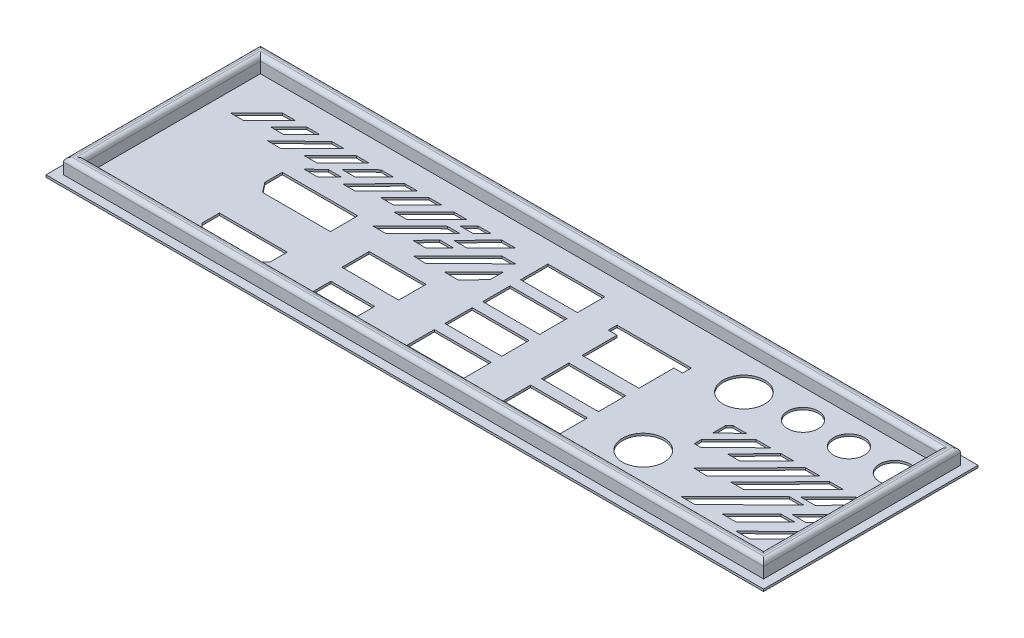
SolidWorks part; units mm, degrees
ref_plane "Front Plane" through (0, 0, 0) normal (0, 0, 1) x (1, 0, 0)
ref_plane "Top Plane" through (0, 0, 0) normal (0, 1, 0) x (1, 0, 0)
ref_plane "Right Plane" through (0, 0, 0) normal (1, 0, 0) x (0, 0, -1)
sketch "Sketch1" plane through (0, 0, 0) normal (0, 1, 0) x (1, 0, 0)
  line L1 (-77.5, -20) -> (77.5, -20)
  line L2 (-77.5, -20) -> (-77.5, 20)
  line L3 (-77.5, 20) -> (77.5, 20)
  line L4 (77.5, -20) -> (77.5, 20)
  line L5 (-77.5, -20) -> (77.5, 20) construction
  line L6 (-77.5, 20) -> (77.5, -20) construction
  point P0 (0, 0)
  dimension "D1" = 40
  dimension "D2" = 155
extrude "Boss-Extrude1" add sketch "Sketch1" along normal blind 0.5
sketch "Sketch2" plane through (0, 0, 0) normal (0, -1, 0) x (1, 0, 0)
  line L0 (-80, 22.5) -> (80, 22.5)
  line L1 (-77.5, -20) -> (77.5, -20)
  line L2 (-77.5, -20) -> (-77.5, 20)
  line L3 (-77.5, 20) -> (77.5, 20)
  line L4 (77.5, -20) -> (77.5, 20)
  line L5 (-77.5, -20) -> (77.5, 20) construction
  line L6 (-77.5, 20) -> (77.5, -20) construction
  line L7 (80, -22.5) -> (80, 22.5)
  line L8 (-80, -22.5) -> (80, -22.5)
  line L9 (-80, -22.5) -> (-80, 22.5)
  point P0 (0, 0)
  dimension "D1" = 2.5
extrude "Boss-Extrude2" add sketch "Sketch2" against normal blind 4
fillet "Fillet1" radius 1 8 edges at (0, 4, -22.5) (80, 4, 0) (0, 4, 22.5) (-80, 4, 0) (0, 4, -20) (-77.5, 4, 0) (0, 4, 20) (77.5, 4, 0)
sketch "Sketch3" plane through (0, 0, 0) normal (0, -1, 0) x (1, 0, 0)
  line L14 (-82, -24.5) -> (82, -24.5)
  line L15 (82, -24.5) -> (82, 24.5)
  line L16 (82, 24.5) -> (-82, 24.5)
  line L17 (-82, 24.5) -> (-82, -24.5)
  line L18 (-82, -24.5) -> (82, -24.5)
  line L19 (82, -24.5) -> (82, 24.5)
  line L20 (82, 24.5) -> (-82, 24.5)
  line L21 (-82, 24.5) -> (-82, -24.5)
  dimension "D1" = 2
extrude "Boss-Extrude3" add sketch "Sketch3" against normal blind 0.5
sketch "Sketch5" plane through (0, 0.5, 0) normal (0, 1, 0) x (1, 0, 0)
  line L0 (77.5, -20) -> (77.5, 20) construction
  line L1 (77.5, 20) -> (-77.5, 20) construction
  line L2 (-77.5, -20) -> (77.5, -20) construction
  line L3 (15, -17) -> (28, -17)
  line L4 (15, -17) -> (15, -10.75)
  line L5 (15, -10.75) -> (28, -10.75)
  line L6 (28, -17) -> (28, -10.75)
  line L7 (15, -8.25) -> (28, -8.25)
  line L8 (15, -8.25) -> (15, -2)
  line L9 (15, -2) -> (28, -2)
  line L10 (28, -8.25) -> (28, -2)
  line L11 (13, 11) -> (13, 9)
  line L12 (13, 9) -> (15, 9)
  line L13 (15, 9) -> (15, 1)
  line L14 (15, 1) -> (28, 1)
  line L15 (28, 1) -> (28, 9)
  line L16 (28, 9) -> (30, 9)
  line L17 (30, 9) -> (30, 11)
  line L18 (30, 11) -> (13, 11)
  line L19 (-77.5, -20) -> (77.5, -20) construction
  line L20 (-7, -17) -> (6, -17)
  line L21 (-7, -17) -> (-7, -10.75)
  line L22 (-7, -10.75) -> (6, -10.75)
  line L23 (6, -17) -> (6, -10.75)
  line L24 (-7, -8.35) -> (6, -8.35)
  line L25 (-7, -8.35) -> (-7, -2.1)
  line L26 (-7, -2.1) -> (6, -2.1)
  line L27 (6, -8.35) -> (6, -2.1)
  line L28 (6, 0.3) -> (-7, 0.3)
  line L29 (6, 0.3) -> (6, 6.55)
  line L30 (6, 6.55) -> (-7, 6.55)
  line L31 (-7, 0.3) -> (-7, 6.55)
  line L32 (-7, 8.95) -> (6, 8.95)
  line L33 (-7, 8.95) -> (-7, 15.2)
  line L34 (-7, 15.2) -> (6, 15.2)
  line L35 (6, 8.95) -> (6, 15.2)
  line L36 (-29.8898, -9) -> (-16.8898, -9)
  line L37 (-29.8898, -9) -> (-29.8898, -2.75)
  line L38 (-29.8898, -2.75) -> (-16.8898, -2.75)
  line L39 (-16.8898, -9) -> (-16.8898, -2.75)
  line L40 (-28.3898, -17) -> (-18.3898, -17)
  line L41 (-28.3898, -17) -> (-28.3898, -13)
  line L42 (-28.3898, -13) -> (-18.3898, -13)
  line L43 (-18.3898, -17) -> (-18.3898, -13)
  line L44 (-55.5, 3) -> (-55.5, -1)
  line L45 (-55.5, -1) -> (-53.75, -3.25)
  line L46 (-53.75, -3.25) -> (-38.25, -3.25)
  line L47 (-38.25, -3.25) -> (-38.25, 3)
  line L48 (-38.25, 3) -> (-55.5, 3)
  line L50 (-39.125, -12.25) -> (-39.125, -16.25)
  line L52 (-41.375, -18.25) -> (-52.375, -18.25)
  line L54 (-54.625, -16.25) -> (-54.625, -12.25)
  line L55 (-41.375, -18.25) -> (-39.125, -16.25)
  line L56 (-52.375, -18.25) -> (-54.625, -16.25)
  line L57 (-77.5, 20) -> (-77.5, -20) construction
  line L58 (-54.625, -12.25) -> (-39.125, -12.25)
  circle A0 centre (74, 13.5) radius 3.5
  circle A1 centre (63.5, 13.5) radius 3.5
  circle A2 centre (53, 13.5) radius 3.5
  circle A3 centre (40.75, 12.25) radius 4.75
  circle A4 centre (40.75, -10.75) radius 4.75
  dimension "D1" = 7
  dimension "D2" = 3.5
  dimension "D4" = 7
  dimension "D5" = 7
  dimension "D6" = 6.5
  dimension "D7" = 6.5
  dimension "D8" = 10.5
  dimension "D9" = 10.5
  dimension "D10" = 9.5
  dimension "D11" = 9.5
  dimension "D12" = 7.75
  dimension "D13" = 23
  dimension "D14" = 36.75
  dimension "D15" = 36.75
  dimension "D3" = 6.5
  dimension "D16" = 6.25
  dimension "D17" = 13
  dimension "D18" = 6.25
  dimension "D19" = 13
  dimension "D20" = 3
  dimension "D21" = 2.5
  dimension "D22" = 3
  dimension "D23" = 13
  dimension "D24" = 8
  dimension "D25" = 2
  dimension "D26" = 2
  dimension "D27" = 2
  dimension "D28" = 2
  dimension "D29" = 49.5
  dimension "D30" = 6.25
  dimension "D31" = 6.25
  dimension "D32" = 6.25
  dimension "D33" = 6.25
  dimension "D34" = 13
  dimension "D35" = 13
  dimension "D36" = 13
  dimension "D37" = 13
  dimension "D38" = 2.4
  dimension "D39" = 2.4
  dimension "D40" = 2.4
  dimension "D41" = 3
  dimension "D42" = 71.5
  dimension "D43" = 13
  dimension "D44" = 6.25
  dimension "D45" = 4
  dimension "D46" = 10
  dimension "D47" = 4
  dimension "D48" = 3
  dimension "D49" = 17.25
  dimension "D50" = 1.5
  dimension "D51" = 6.25
  dimension "D52" = 15.5
  dimension "D53" = 15.5
  dimension "D54" = 9
  dimension "D55" = 11
  dimension "D56" = 4
  dimension "D57" = 4
  dimension "D58" = 2.25
  dimension "D59" = 0.875
  dimension "D60" = 22
  dimension "D61" = 17
  dimension "D62" = 4
  dimension "D63" = 6
extrude "Cut-Extrude1" cut sketch "Sketch5" against normal through all
sketch "Sketch7" plane through (0, 0.5, 0) normal (0, 1, 0) x (1, 0, 0)
  line L0 (-67.2505, 14.7466) -> (-64.2392, 14.7466)
  line L1 (-64.2392, 14.7466) -> (-70.1769, 8.8089)
  line L2 (-70.1769, 8.8089) -> (-73.2004, 8.8089)
  line L3 (-73.2004, 8.8089) -> (-67.2505, 14.7466)
  line L4 (-61.6406, 14.7466) -> (-58.7264, 14.7466)
  line L5 (-58.7264, 14.7466) -> (-62.859, 10.6224)
  line L6 (-62.859, 10.6224) -> (-65.7448, 10.6224)
  line L7 (-65.7448, 10.6224) -> (-61.6406, 14.7466)
  line L8 (-55.8851, 14.7466) -> (-53.1651, 14.7466)
  line L9 (-53.1651, 14.7466) -> (-60.336, 7.5408)
  line L10 (-60.336, 7.5408) -> (-63.4377, 7.5408)
  line L11 (-63.4377, 7.5408) -> (-55.8851, 14.7466)
  line L12 (-50.3238, 14.7466) -> (-47.4096, 14.7466)
  line L13 (-47.4096, 14.7466) -> (-53.3185, 8.8089)
  line L14 (-53.3185, 8.8089) -> (-56.3465, 8.8089)
  line L15 (-56.3465, 8.8089) -> (-50.3238, 14.7466)
  line L16 (-44.7382, 14.7466) -> (-41.8968, 14.7466)
  line L17 (-41.8968, 14.7466) -> (-46.3352, 10.3708)
  line L18 (-46.3352, 10.3708) -> (-49.2795, 10.3708)
  line L19 (-49.2795, 10.3708) -> (-44.7382, 14.7466)
  line L20 (-50.7366, 8.8089) -> (-47.8074, 8.8089)
  line L21 (-47.8074, 8.8089) -> (-50.6074, 6.1109)
  line L22 (-50.6074, 6.1109) -> (-53.6866, 6.1109)
  line L23 (-53.6866, 6.1109) -> (-50.7366, 8.8089)
  line L24 (-39.2255, 14.7466) -> (-36.2627, 14.7466)
  line L25 (-36.2627, 14.7466) -> (-43.4147, 7.5946)
  line L26 (-43.4147, 7.5946) -> (-46.3352, 7.5946)
  line L27 (-46.3352, 7.5946) -> (-39.2255, 14.7466)
  line L28 (-33.567, 14.7466) -> (-30.7742, 14.7466)
  line L29 (-30.7742, 14.7466) -> (-36.2627, 9.2256)
  line L30 (-36.2627, 9.2256) -> (-39.2255, 9.2256)
  line L31 (-39.2255, 9.2256) -> (-33.737, 14.7466)
  line L32 (-33.737, 14.7466) -> (-33.567, 14.7466)
  line L33 (-28.0398, 14.7466) -> (-25.0141, 14.7466)
  line L34 (-25.0141, 14.7466) -> (-31.833, 7.8872)
  line L35 (-31.833, 7.8872) -> (-34.9164, 7.8872)
  line L36 (-34.9164, 7.8872) -> (-28.0398, 14.7466)
  line L37 (-22.5741, 14.7466) -> (-19.5809, 14.7466)
  line L38 (-19.5809, 14.7466) -> (-21.648, 12.6846)
  line L39 (-21.648, 12.6846) -> (-24.461, 12.6846)
  line L40 (-24.461, 12.6846) -> (-22.5741, 14.7466)
  line L41 (-25.9576, 11.1706) -> (-23.0545, 11.1706)
  line L42 (-23.0545, 11.1706) -> (-31.5441, 2.7023)
  line L43 (-31.5441, 2.7023) -> (-34.563, 2.7023)
  line L44 (-34.563, 2.7023) -> (-25.9576, 11.1706)
  line L45 (-27.0963, 4.4196) -> (-24.1194, 4.4196)
  line L46 (-24.1194, 4.4196) -> (-20.893, 7.5946)
  line L47 (-20.893, 7.5946) -> (-24.1194, 7.5946)
  line L48 (-24.1194, 7.5946) -> (-27.0963, 4.4196)
  line L49 (-22.3788, 9.1044) -> (-19.4508, 9.1044)
  line L50 (-19.4508, 9.1044) -> (-13.8097, 14.6556)
  line L51 (-13.8097, 14.6556) -> (-17.0595, 14.6556)
  line L52 (-17.0595, 14.6556) -> (-22.3788, 9.1044)
  line L53 (-23.8985, 1.4213) -> (-21.0775, 1.3284)
  line L54 (-21.0775, 1.3284) -> (-10.7225, 11.5185)
  line L55 (-10.7225, 11.5185) -> (-13.8097, 11.5185)
  line L56 (-13.8097, 11.5185) -> (-23.8985, 1.4213)
  line L57 (-17.271, 1.7843) -> (-14.1646, 1.7843)
  line L58 (-14.1646, 1.7843) -> (-10.4894, 5.4625)
  line L59 (-10.4894, 5.4625) -> (-10.4894, 8.584)
  line L60 (-10.4894, 8.584) -> (-17.271, 1.7843)
  line L61 (45.286, 3.6234) -> (45.286, 0.5133)
  line L62 (45.286, 0.5133) -> (49.2028, 4.3678)
  line L63 (49.2028, 4.3678) -> (46.1452, 4.3678)
  line L64 (46.1452, 4.3678) -> (45.286, 3.6234)
  line L65 (45.286, -2.027) -> (45.286, -3.6334)
  line L66 (45.286, -3.6334) -> (46.8176, -3.6334)
  line L67 (46.8176, -3.6334) -> (54.8194, 4.241)
  line L68 (54.8194, 4.241) -> (51.562, 4.241)
  line L69 (51.562, 4.241) -> (45.286, -2.027)
  line L70 (51.1884, -1.8776) -> (53.9902, -1.8776)
  line L71 (53.9902, -1.8776) -> (60.1956, 4.3198)
  line L72 (60.1956, 4.3198) -> (57.0929, 4.3198)
  line L73 (57.0929, 4.3198) -> (51.1884, -1.8776)
  line L74 (50.0677, -8.5085) -> (53.0574, -8.607)
  line L75 (53.0574, -8.607) -> (66.0007, 4.3198)
  line L76 (66.0007, 4.3198) -> (62.7505, 4.3198)
  line L77 (62.7505, 4.3198) -> (50.0677, -8.5085)
  line L78 (68.2421, 4.3198) -> (71.3054, 4.3198)
  line L79 (71.3054, 4.3198) -> (60.0337, -7.0812)
  line L80 (60.0337, -7.0812) -> (57.0929, -7.0812)
  line L81 (57.0929, -7.0812) -> (68.2421, 4.3198)
  line L82 (74.2358, 4.241) -> (75.9516, 4.241)
  line L83 (75.9516, 4.241) -> (75.9516, 2.7023)
  line L84 (75.9516, 2.7023) -> (71.3054, -2.0489)
  line L85 (71.3054, -2.0489) -> (68.0517, -2.0489)
  line L86 (68.0517, -2.0489) -> (74.2358, 4.241)
  line L87 (75.8086, -1.2317) -> (75.8086, -4.2522)
  line L88 (75.8086, -4.2522) -> (73.5745, -6.4864)
  line L89 (73.5745, -6.4864) -> (70.5182, -6.4864)
  line L90 (70.5182, -6.4864) -> (75.7729, -1.2317)
  line L91 (75.8086, -7.9698) -> (75.8086, -10.8831)
  line L92 (75.8086, -10.8831) -> (70.5182, -16.1735)
  line L93 (70.5182, -16.1735) -> (67.3547, -16.1735)
  line L94 (67.3547, -16.1735) -> (75.8086, -7.9698)
  line L95 (69.0883, -7.666) -> (72.3055, -7.666)
  line L96 (72.3055, -7.666) -> (65.603, -14.3685)
  line L97 (65.603, -14.3685) -> (62.4753, -14.3685)
  line L98 (62.4753, -14.3685) -> (69.0883, -7.666)
  line L99 (66.6219, -3.2513) -> (69.982, -3.2513)
  line L100 (69.982, -3.2513) -> (57.3994, -15.6195)
  line L101 (57.3994, -15.6195) -> (54.2001, -15.6195)
  line L102 (54.2001, -15.6195) -> (66.6219, -3.2513)
  line L103 (75.7729, -1.2317) -> (75.8086, -1.2317)
extrude "Cut-Extrude2" cut sketch "Sketch7" against normal through all
